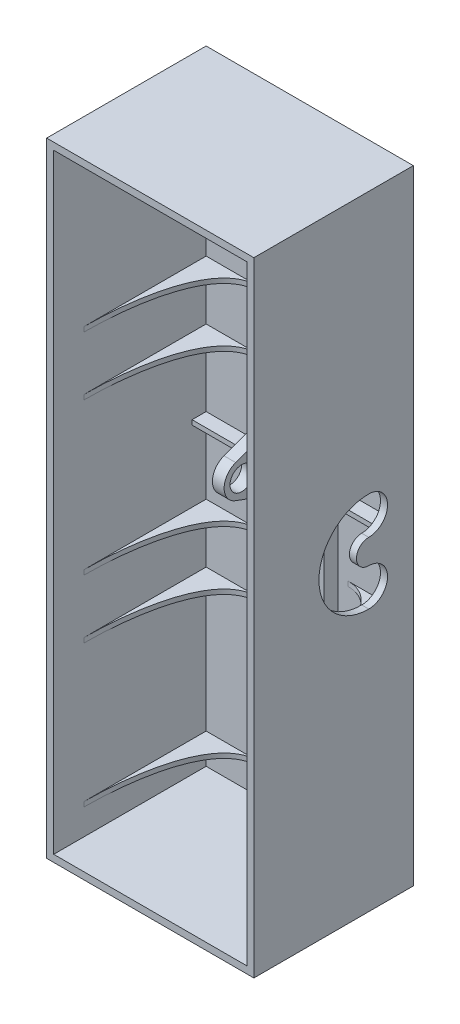
SolidWorks part; units mm, degrees
ref_plane "Front Plane" through (0, 0, 0) normal (0, 0, 1) x (1, 0, 0)
ref_plane "Top Plane" through (0, 0, 0) normal (0, 1, 0) x (1, 0, 0)
ref_plane "Right Plane" through (0, 0, 0) normal (1, 0, 0) x (0, 0, -1)
sketch "Sketch1" plane through (0, 0, 0) normal (0, 0, 1) x (1, 0, 0)
  line L0 (0, 263) -> (0, 0)
  line L1 (0, 0) -> (88.35, 0)
  line L3 (3, 3) -> (85.35, 3)
  line L7 (0, 263) -> (3, 263)
  line L8 (3, 3) -> (3, 263)
  line L11 (85.35, 3) -> (85.35, 263.0928)
  line L12 (85.35, 263.0928) -> (88.35, 263.0928)
  line L13 (88.35, 0) -> (88.35, 263.0928)
  dimension "D1" = 3
  dimension "D2" = 3
  dimension "D3" = 260
  dimension "D4" = 82.35
  dimension "D5" = 3
extrude "Boss-Extrude1" add sketch "Sketch1" along normal blind 68
sketch "Sketch2" plane through (0, 0, 0) normal (0, 0, 1) x (1, 0, 0)
  line L1 (0, 263) -> (88.35, 263)
  line L2 (0, 263) -> (0, 0)
  line L3 (0, 0) -> (88.35, 0)
  line L4 (88.35, 263) -> (88.35, 0)
extrude "Boss-Extrude2" add sketch "Sketch2" along normal blind 3
ref_plane "Plane1" through (34.175, 0, 0) normal (1, 0, 0) x (0, 0, -1)
sketch "Sketch3" plane through (34.175, 0, 0) normal (1, 0, 0) x (0, 0, -1)
  line L2 (-21.5652, 140.0477) -> (-3, 146.8049)
  line L3 (-3, 3) -> (-3, 263) construction
  line L4 (-3, 146.8049) -> (-3, 119.1951)
  line L5 (-3, 119.1951) -> (-21.5652, 125.9523)
  line L7 (-68, 3) -> (-3, 3) construction
  arc A0 (-21.5652, 140.0477) -> (-21.5652, 125.9523) centre (-19, 133) ccw
  circle A1 centre (-19, 133) radius 5
  dimension "D2" = 15
  dimension "D5" = 10
  dimension "D1" = 16
  dimension "D3" = 130
  dimension "D4" = 70
extrude "Boss-Extrude3" add sketch "Sketch3" against normal blind 5
ref_plane "Plane2" through (54.175, 0, 0) normal (1, 0, 0) x (0, 0, -1)
sketch "Sketch6" plane through (54.175, 0, 0) normal (1, 0, 0) x (0, 0, -1)
  line L0 (-19, 138) -> (-3, 138)
  line L2 (-3, 138) -> (-3, 128)
  line L3 (-3, 128) -> (-19, 128)
  line L4 (-3, 263) -> (-3, 3) construction
  arc A0 (-19, 138) -> (-19, 128) centre (-19, 133) ccw
  circle A1 centre (-19, 133) radius 5 construction
extrude "Boss-Extrude6" add sketch "Sketch6" along normal blind 8
hole_wizard "M6 Clearance Hole1" positions "Sketch7" profile "Sketch8" hole size "M6" standard "ISO"
sketch "Sketch7" plane through (54.175, 0, 0) normal (-1, 0, 0) x (0, 0, 1)
  arc A0 (19, 128) -> (19, 138) centre (19, 133) ccw construction
  point P0 (19, 133)
sketch "Sketch8" plane through (54.175, 133, 19) normal (0, 1, 0) x (0, 0, 1)
  line L0 (0, 0) -> (0, 8)
  line L1 (0, 8) -> (3.3, 8)
  line L2 (3.3, 8) -> (3.3, 0)
  line L5 (3.3, 0) -> (0, 0)
  line L11 (0, -6.35) -> (0, 107.95) construction
  dimension "Thru Hole Dia." = 6.6
  dimension "Thru Hole Depth" = 8
sketch "Sketch10" plane through (85.35, 0, 0) normal (-1, 0, 0) x (0, 0, 1)
  line L2 (3, 263) -> (3, 3) construction
  line L4 (19, 146.25) -> (19, 119.75) construction
  arc A0 (19, 146.25) -> (19, 119.75) centre (19, 133) cw construction
  arc A1 (19, 111.75) -> (19, 154.25) centre (19, 133) ccw
  arc A2 (19, 127.75) -> (19, 138.25) centre (19, 133) ccw
  arc A3 (19, 127.75) -> (19, 111.75) centre (19, 119.75) ccw
  arc A4 (19, 154.25) -> (19, 138.25) centre (19, 146.25) ccw
  point P5 (32.25, 133)
  point P20 (3, 133)
  dimension "D3" = 8
  dimension "D1" = 16
  dimension "D2" = 13.25
extrude "Cut-Extrude1" cut sketch "Sketch10" against normal up to next
sketch "Sketch11" plane through (0, 263, 0) normal (0, 1, 0) x (1, 0, 0)
  line L4 (0, 0) -> (0, -68)
  line L5 (88.35, 0) -> (0, 0)
  line L6 (88.35, -68) -> (88.35, 0)
  line L7 (0, -68) -> (88.35, -68)
  line L8 (0, 0) -> (0, -68)
  line L9 (88.35, 0) -> (0, 0)
  line L10 (88.35, -68) -> (88.35, 0)
  line L11 (0, -68) -> (88.35, -68)
  dimension "D1" = 0
extrude "Boss-Extrude7" add sketch "Sketch11" along normal blind 3
ref_plane "Plane4" through (44.175, 0, 0) normal (1, 0, 0) x (0, 0, -1)
sketch "Sketch13" plane through (0, 0, 3) normal (0, 0, 1) x (1, 0, 0)
  line L0 (3, 3) -> (3, 263) construction
  line L1 (3, 251.9797) -> (24.8525, 251.9797)
  line L2 (3, 251.9797) -> (3, 249.9797)
  line L3 (3, 249.9797) -> (24.8525, 249.9797)
  line L4 (24.8525, 251.9797) -> (24.8525, 249.9797)
  line L5 (3, 3) -> (3, 263) construction
  line L6 (3, 191.4189) -> (24.8525, 191.4189)
  line L7 (3, 191.4189) -> (3, 189.4189)
  line L8 (3, 189.4189) -> (24.8525, 189.4189)
  line L9 (24.8525, 191.4189) -> (24.8525, 189.4189)
  line L10 (3, 166.3498) -> (24.8525, 166.3498)
  line L11 (3, 166.3498) -> (3, 164.3498)
  line L12 (3, 164.3498) -> (24.8525, 164.3498)
  line L13 (24.8525, 166.3498) -> (24.8525, 164.3498)
  line L14 (3, 133) -> (85.35, 133) construction
  line L15 (85.35, 263) -> (85.35, 3) construction
  line L16 (3, 16.0203) -> (24.8525, 16.0203)
  line L17 (24.8525, 14.0203) -> (24.8525, 16.0203)
  line L18 (3, 14.0203) -> (24.8525, 14.0203)
  line L19 (3, 14.0203) -> (3, 16.0203)
  line L20 (3, 76.5811) -> (24.8525, 76.5811)
  line L21 (24.8525, 74.5811) -> (24.8525, 76.5811)
  line L22 (3, 74.5811) -> (24.8525, 74.5811)
  line L23 (3, 74.5811) -> (3, 76.5811)
  line L24 (3, 101.6502) -> (24.8525, 101.6502)
  line L25 (24.8525, 99.6502) -> (24.8525, 101.6502)
  line L26 (3, 99.6502) -> (24.8525, 99.6502)
  line L27 (3, 99.6502) -> (3, 101.6502)
  dimension "D1" = 2
extrude "Boss-Extrude8" add sketch "Sketch13" along normal blind 52
sketch "Sketch14" plane through (0, 14.0203, 0) normal (0, -1, 0) x (1, 0, 0)
  line L0 (3, 3) -> (24.8525, 3) construction
  line L1 (3, 55) -> (3, 3) construction
  line L2 (24.8525, 3) -> (24.8525, 55)
  line L3 (24.8525, 55) -> (3, 55)
  spline S0 degree 3 poles (3, 55) (3, 38.0721) (6.2716, 3) (24.8525, 3) knots 0 0 0 0 1 1 1 1
extrude "Cut-Extrude2" cut sketch "Sketch14" against normal up to surface (237.9595 mm away) up to face at (13.9263, 251.9797, 29)
mirror "Mirror3" about plane through (44.175, 0, 0) normal (1, 0, 0) of "Boss-Extrude8", "Cut-Extrude2"
sketch "Sketch15" plane through (0, 0, 3) normal (0, 0, 1) x (1, 0, 0)
  line L0 (85.35, 263) -> (3, 263) construction
  line L1 (30.675, 263) -> (32.675, 263)
  line L2 (30.675, 263) -> (30.675, 3)
  line L3 (30.675, 3) -> (32.675, 3)
  line L4 (32.675, 263) -> (32.675, 3)
  line L5 (85.35, 3) -> (3, 3) construction
  line L6 (29.175, 119.1951) -> (34.175, 119.1951) construction
  line L7 (3, 263) -> (85.35, 263) construction
  line L8 (59.175, 263) -> (57.175, 263)
  line L9 (59.175, 263) -> (59.175, 3)
  line L10 (59.175, 3) -> (57.175, 3)
  line L11 (57.175, 263) -> (57.175, 3)
  line L12 (62.175, 128) -> (54.175, 128) construction
  line L13 (29.175, 119.1951) -> (29.175, 146.8049) construction
  line L14 (29.175, 134) -> (3, 134)
  line L15 (29.175, 134) -> (29.175, 132)
  line L16 (29.175, 132) -> (3, 132)
  line L17 (3, 134) -> (3, 132)
  line L18 (3, 101.6502) -> (3, 164.3498) construction
  line L19 (62.175, 128) -> (62.175, 138) construction
  line L20 (62.175, 134) -> (85.35, 134)
  line L21 (62.175, 134) -> (62.175, 132)
  line L22 (62.175, 132) -> (85.35, 132)
  line L23 (85.35, 134) -> (85.35, 132)
  line L24 (85.35, 263) -> (85.35, 3) construction
  line L25 (29.175, 140.0477) -> (29.175, 125.9523) construction
  point P10 (31.675, 119.1951)
  point P11 (31.675, 3)
  point P18 (58.175, 3)
  point P21 (58.175, 128)
  point P38 (62.175, 133)
  point P39 (29.175, 133)
  dimension "D1" = 2
extrude "Boss-Extrude9" add sketch "Sketch15" along normal blind 6
sketch "Sketch16" plane through (0, 0, 3) normal (0, 0, 1) x (1, 0, 0)
  line L1 (36.675, 258) -> (51.675, 258)
  line L2 (36.675, 258) -> (36.675, 208)
  line L3 (36.675, 208) -> (51.675, 208)
  line L4 (51.675, 258) -> (51.675, 208)
  line L5 (54.175, 138) -> (54.175, 128) construction
  line L7 (34.175, 133) -> (54.175, 133) construction
  line L8 (34.175, 119.1951) -> (34.175, 146.8049) construction
  line L9 (36.675, 58) -> (51.675, 58)
  line L10 (51.675, 8) -> (51.675, 58)
  line L11 (36.675, 8) -> (51.675, 8)
  line L12 (36.675, 8) -> (36.675, 58)
  line L13 (88.35, 266) -> (0, 266) construction
  point P10 (54.175, 133)
  point P11 (51.675, 233)
  point P20 (44.175, 266)
  point P21 (44.175, 258)
  dimension "D1" = 15
  dimension "D2" = 50
  dimension "D3" = 100
extrude "Boss-Extrude10" add sketch "Sketch16" along normal blind 4
hole_wizard "M6 Tapped Hole2" positions "Sketch17" profile "Sketch18" tap size "M6" standard "ISO" end condition up to next
sketch "Sketch17" plane through (0, 0, 7) normal (0, 0, 1) x (1, 0, 0)
  line L0 (51.675, 258) -> (36.675, 258) construction
  line L1 (36.675, 208) -> (51.675, 208) construction
  line L2 (51.675, 58) -> (36.675, 58) construction
  line L3 (36.675, 8) -> (51.675, 8) construction
  point P0 (44.175, 250.24)
  point P2 (44.175, 215.76)
  point P4 (44.175, 50.24)
  point P6 (44.175, 15.76)
  point P18 (44.175, 8)
  dimension "D1" = 7.76
  dimension "D2" = 7.76
  dimension "D3" = 7.76
  dimension "D4" = 7.76
sketch "Sketch18" plane through (44.175, 250.24, 7) normal (1, 0, 0) x (0, -1, 0)
  line L0 (0, 0) -> (0, 7)
  line L1 (0, 7) -> (2.5, 7)
  line L2 (2.5, 7) -> (2.5, 0)
  line L5 (2.5, 0) -> (0, 0)
  line L11 (0, -6.35) -> (0, 107.95) construction
  dimension "Thru Tap Drill Dia." = 5
  dimension "Thru Tap Drill Depth" = 7
cosmetic thread "Hole Thread2" parameters "D2"=6
cosmetic thread "Hole Thread3" parameters "D2"=6
cosmetic thread "Hole Thread4" parameters "D2"=6
cosmetic thread "Hole Thread5" parameters "D2"=6
